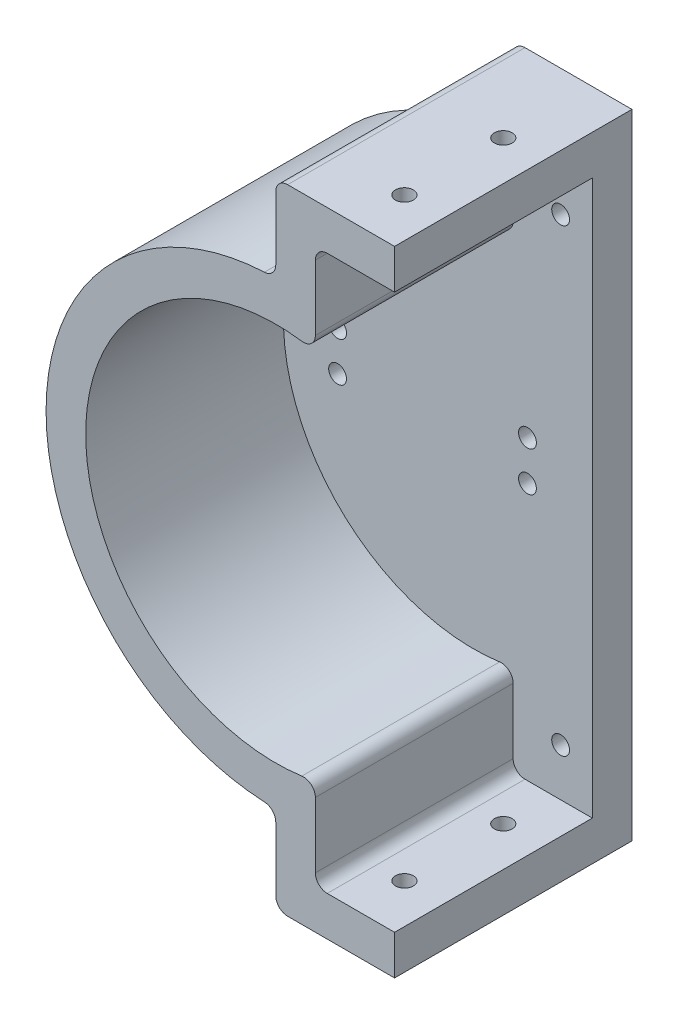
SolidWorks part; units mm, degrees
ref_plane "Front Plane" through (0, 0, 0) normal (1, 0, 0) x (0, 1, 0)
ref_plane "Top Plane" through (0, 0, 0) normal (0, 0, 1) x (0, 1, 0)
ref_plane "Right Plane" through (0, 0, 0) normal (0, 1, 0) x (-1, 0, 0)
sketch "Sketch1" plane through (0, 0, 0) normal (0, 0, 1) x (0, 1, 0)
  line L0 (0, 0) -> (0, -100) construction
  line L4 (-100.8861, 0) -> (100.8861, 0) construction
  line L12 (-58, 0) -> (-80, 0)
  line L13 (-80, 0) -> (-80, -30)
  line L14 (80, 0) -> (80, -30)
  line L15 (58, 0) -> (80, 0)
  line L16 (-80, -30) -> (80, -30)
  arc A1 (58, 0) -> (-58, 0) centre (0, 0) ccw
  dimension "D1" = 58
  dimension "D2" = 22
  dimension "D5" = 30
extrude "Boss-Extrude2" add sketch "Sketch1" along normal blind 10
sketch "Sketch3" plane through (0, 0, 10) normal (0, 0, 1) x (1, 0, 0)
  line L0 (-24.0732, 0) -> (18.5092, 0) construction
  line L1 (0, 7.3017) -> (0, -5.8366) construction
  circle A0 centre (0, 0) radius 48 construction
  circle A1 centre (13.625, -5) radius 2.25
  circle A2 centre (-34.325, -5) radius 2.25
  circle A3 centre (-34.325, 5) radius 2.25
  circle A4 centre (13.625, 5) radius 2.25
  dimension "D1" = 96
  dimension "D2" = 4.5
  dimension "D5" = 47.95
  dimension "D3" = 5
  dimension "D4" = 13.625
extrude "Cut-Extrude2" cut sketch "Sketch3" against normal through all
sketch "Sketch4" plane through (0, 0, 0) normal (0, 0, -1) x (1, 0, 0)
  circle A0 centre (-34.325, -5) radius 3.6
  circle A1 centre (-34.325, 5) radius 3.6
  circle A2 centre (13.625, 5) radius 3.6
  circle A3 centre (13.625, -5) radius 3.6
  dimension "D1" = 7.2
extrude "Cut-Extrude3" cut sketch "Sketch4" against normal blind 5
sketch "Sketch5" plane through (0, 0, 10) normal (0, 0, 1) x (1, 0, 0)
  line L0 (10, -46.9468) -> (10, -70)
  line L3 (0, 80) -> (0, 58)
  line L4 (0, 80) -> (0, 58)
  line L5 (0, -58) -> (0, -80)
  line L13 (10, -70) -> (20, -70)
  line L16 (20, 70) -> (10, 70)
  line L17 (10, 70) -> (10, 46.9468)
  line L18 (20, 70) -> (30, 70)
  line L19 (20, -70) -> (30, -70)
  line L20 (30, 70) -> (30, 80)
  line L21 (30, -80) -> (30, 80) construction
  line L24 (0, -58) -> (0, -80)
  line L25 (0, -80) -> (30, -80)
  line L26 (0, -80) -> (30, -80)
  line L27 (30, -80) -> (30, 80)
  line L28 (30, -80) -> (30, -70)
  line L29 (30, 80) -> (0, 80)
  line L30 (30, 80) -> (0, 80)
  line L33 (20, -70) -> (20, 70) construction
  arc A1 (0, 58) -> (0, -58) centre (0, 0) ccw
  arc A2 (0, 58) -> (0, -58) centre (0, 0) ccw
  arc A3 (10, 46.9468) -> (10, -46.9468) centre (0, 0) ccw
  dimension "D2" = 10
  dimension "D1" = 0
extrude "Boss-Extrude4" add sketch "Sketch5" along normal blind 49.94
sketch "Sketch7" plane through (0, -70, 0) normal (0, 1, 0) x (-1, 0, 0)
  line L0 (-30, 34.97) -> (8.3655, 34.97) construction
  line L1 (-30, 59.94) -> (-30, 10) construction
  circle A0 centre (-20, 47.455) radius 2.25
  circle A1 centre (-20, 22.485) radius 2.25
  dimension "D2" = 4.5
  dimension "D1" = 12.485
  dimension "D3" = 10
extrude "Cut-Extrude5" cut sketch "Sketch7" against normal through all both and the other way through all
sketch "Sketch8" plane through (0, 0, 10) normal (0, 0, 1) x (1, 0, 0)
  line L0 (10, -70) -> (10, -46.9468) construction
  line L2 (30, -70) -> (10, -70) construction
  line L3 (32.967, 0) -> (-32.967, 0) construction
  circle A0 centre (22, -58) radius 2.25
  circle A1 centre (22, 58) radius 2.25
  dimension "D1" = 4.5
  dimension "D2" = 12
  dimension "D3" = 12
extrude "Cut-Extrude6" cut sketch "Sketch8" against normal through all both and the other way through all
fillet "Fillet1" radius 3 8 edges at (0, 58, 29.97) (0, 80, 29.97) (10, 70, 34.97) (10, 46.9468, 34.97) (10, -46.9468, 34.97) (0, -58, 29.97) (0, -80, 29.97) (10, -70, 34.97)
sketch "Sketch9" plane through (0, 0, 0) normal (0, 0, -1) x (1, 0, 0)
  line L0 (-32.967, 0) -> (32.967, 0) construction
  circle A0 centre (22, 58) radius 3.6
  circle A1 centre (22, -58) radius 3.6
  dimension "D1" = 7.2
extrude "Cut-Extrude7" cut sketch "Sketch9" against normal blind 5 and the other way through all
